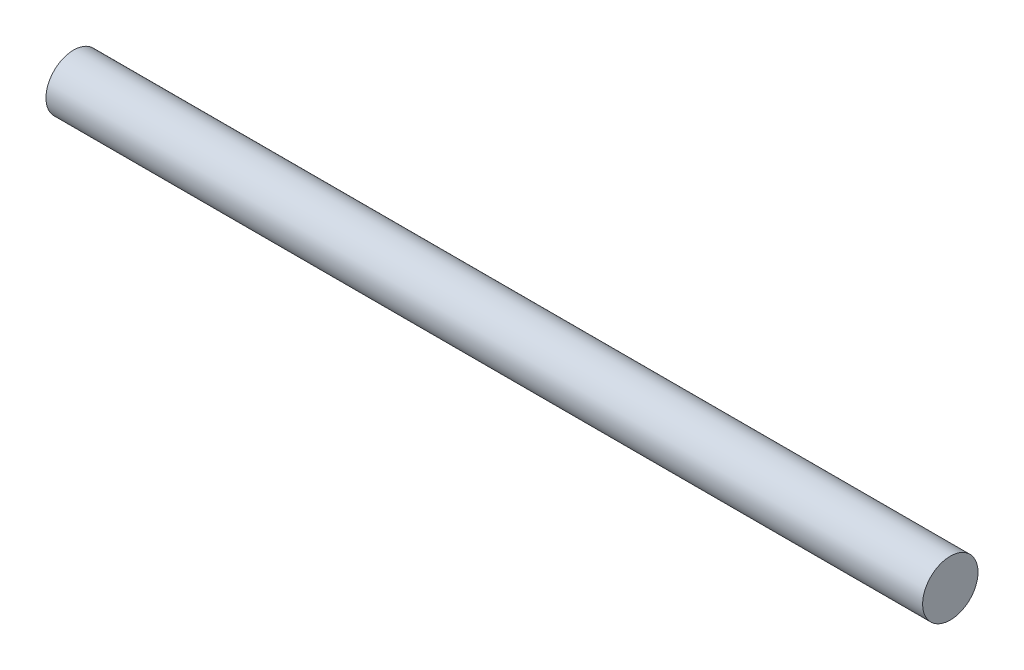
SolidWorks part; units mm, degrees
ref_plane "Front Plane" through (0, 0, 0) normal (0, 0, 1) x (1, 0, 0)
ref_plane "Top Plane" through (0, 0, 0) normal (0, 1, 0) x (1, 0, 0)
ref_plane "Right Plane" through (0, 0, 0) normal (1, 0, 0) x (0, 0, -1)
sketch "Sketch1" plane through (0, 0, 0) normal (1, 0, 0) x (0, 0, -1)
  circle A0 centre (0, 0) radius 2.4
  dimension "D1" = 4.8
extrude "Boss-Extrude1" add sketch "Sketch1" along normal mid plane 76 contours A0
sketch "Sketch2" plane through (0, 0, 0) normal (1, 0, 0) x (0, 0, -1)
  line L0 (0, 2.631) -> (0, -2.631) construction
  line L1 (0, 2.64) -> (0, -2.64) construction
